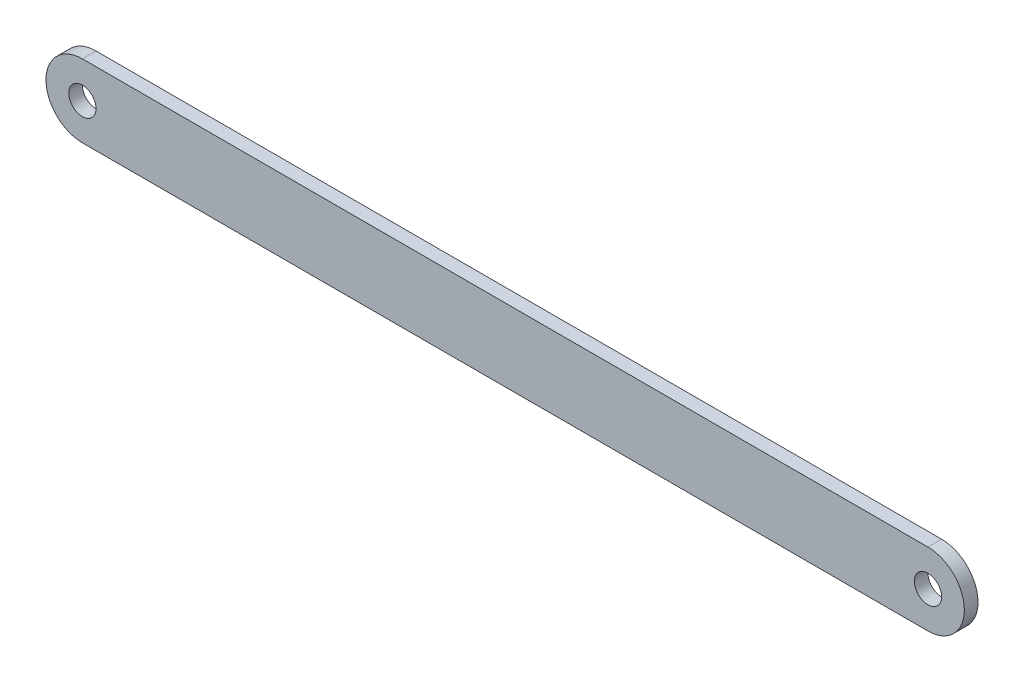
SolidWorks part; units mm, degrees
ref_plane "前视基准面" through (0, 0, 0) normal (0, 0, 1) x (1, 0, 0)
ref_plane "上视基准面" through (0, 0, 0) normal (0, 1, 0) x (1, 0, 0)
ref_plane "右视基准面" through (0, 0, 0) normal (1, 0, 0) x (0, 0, -1)
other "Configuration Table"
sketch "草图1" plane through (0, 0, 0) normal (0, 0, 1) x (1, 0, 0)
  line L0 (0, 0) -> (98934.0575, 0) construction
  line L1 (0, 0) -> (0, 98934.0575) construction
  line L3 (-101, 8) -> (101, 8)
  line L4 (-101, 8) -> (-101, -8)
  line L5 (-101, -8) -> (101, -8)
  line L6 (101, 8) -> (101, -8)
  circle A0 centre (-93, 0) radius 8
  circle A1 centre (93, 0) radius 8
  circle A2 centre (-93, 0) radius 3
  circle A3 centre (93, 0) radius 3
  dimension "D1" = 202
  dimension "D2" = 16
extrude "凸台-拉伸1" add sketch "草图1" along normal blind 3 contours A1 L3 A0 L5 | A0 A2 | A1 A3
